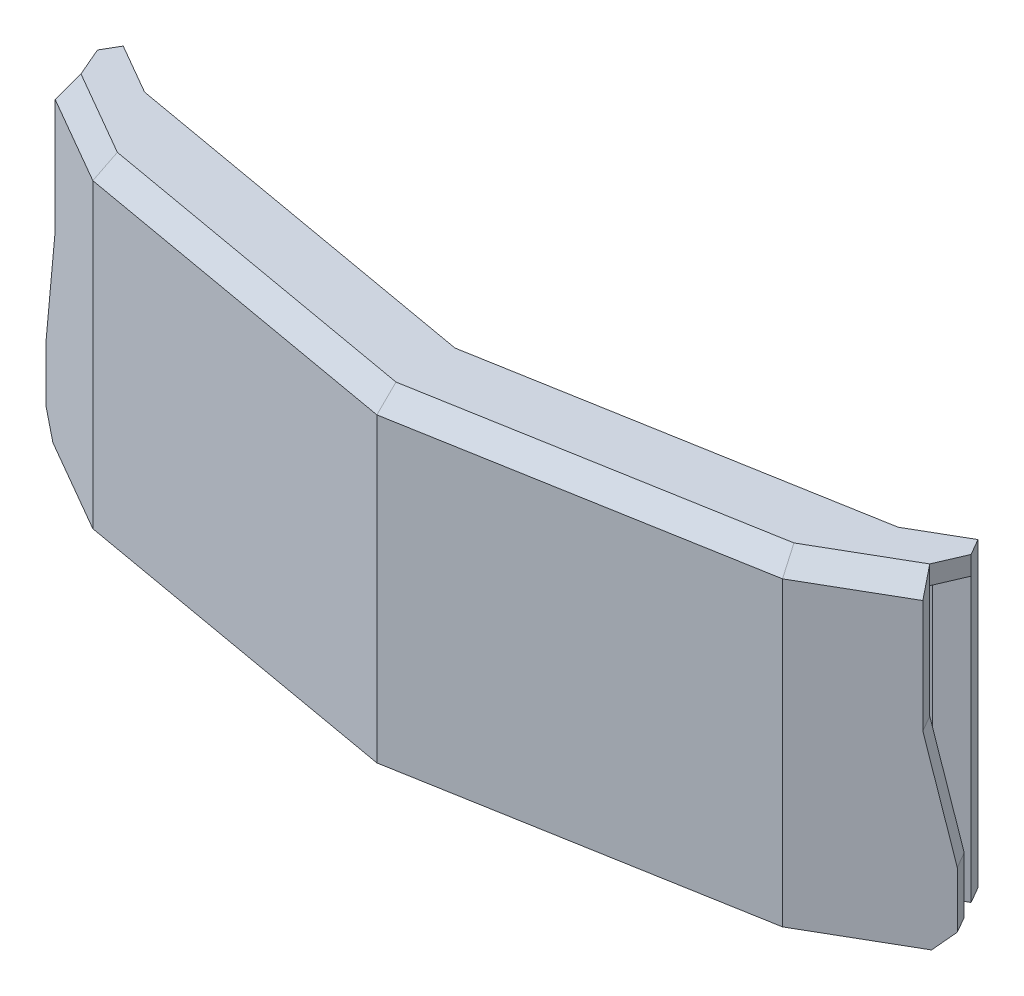
SolidWorks part; units mm, degrees
ref_plane "Front Plane" through (0, 0, 0) normal (0, 0, 1) x (1, 0, 0)
ref_plane "Top Plane" through (0, 0, 0) normal (0, 1, 0) x (1, 0, 0)
ref_plane "Right Plane" through (0, 0, 0) normal (1, 0, 0) x (0, 0, -1)
sketch "Sketch1" plane through (0, 0, 0) normal (0, 1, 0) x (1, 0, 0)
  line L0 (-46.3723, 14.6809) -> (-42.0422, 12.1809)
  line L1 (-42.0422, 12.1809) -> (-43.0422, 10.4488)
  line L2 (-43.0422, 10.4488) -> (-47.3723, 12.9488)
  line L3 (-47.3723, 12.9488) -> (-48.3723, 11.2168)
  line L4 (-48.3723, 11.2168) -> (-36.6067, 4.4239)
  line L5 (-36.6067, 4.4239) -> (0, -2.0309)
  line L6 (0, -2.0309) -> (36.6067, 4.4239)
  line L7 (46.3723, 14.6809) -> (42.0422, 12.1809)
  line L8 (42.0422, 12.1809) -> (43.0422, 10.4488)
  line L9 (43.0422, 10.4488) -> (47.3723, 12.9488)
  line L10 (47.3723, 12.9488) -> (48.3723, 11.2168)
  line L11 (48.3723, 11.2168) -> (36.6067, 4.4239)
  line L12 (-40, 8.6924) -> (-35.9121, 6.3323)
  line L13 (-35.9121, 6.3323) -> (0, 0)
  line L14 (0, 0) -> (35.9121, 6.3323)
  line L15 (35.9121, 6.3323) -> (40, 8.6924)
  line L18 (-40, 13.3112) -> (-45.3723, 16.4129)
  line L19 (-45.3723, 16.4129) -> (-46.3723, 14.6809)
  line L20 (40, 13.3112) -> (45.3723, 16.4129)
  line L21 (45.3723, 16.4129) -> (46.3723, 14.6809)
  line L22 (40, 13.3112) -> (40, 8.6924)
  line L23 (-40, 13.3112) -> (-40, 8.6924)
  dimension "D1" = 2
  dimension "D2" = 2
  dimension "D3" = 6.2034
  dimension "D4" = 2
  dimension "D5" = 80
  dimension "D6" = 2
  dimension "D7" = 6
  dimension "D8" = 6
  dimension "D9" = 13.5857
  dimension "D10" = 36.6067
  dimension "D11" = 4.4239
  dimension "D12" = 6.3323
  dimension "D13" = 13.5857
  dimension "D14" = 5
  dimension "D15" = 160
  dimension "D16" = 6.2034
  dimension "D17" = 5
  dimension "D18" = 160
  dimension "D19" = 160
extrude "Boss-Extrude2" add sketch "Sketch1" along normal blind 32
sketch "Sketch8" plane through (-6.2361, 0, 10.8012) normal (0.5, 0, -0.866) x (-0.866, 0, -0.5)
  line L25 (44.821, 32) -> (47.5, 32)
  line L26 (41.2966, 32) -> (47.5, 32) construction
  line L27 (47.5, 32) -> (47.5, 7.9443)
  line L28 (47.5, 32) -> (47.5, 0) construction
  line L29 (47.5, 7.9443) -> (44.821, 20)
  line L31 (44.821, 32) -> (44.821, 20)
  dimension "D1" = 102.529
  dimension "D2" = 12
  dimension "D3" = 2.679
sketch "Sketch9" plane through (6.2361, 0, 10.8012) normal (-0.5, 0, -0.866) x (-0.866, 0, 0.5)
  line L0 (-44.821, 20) -> (-47.5, 7.9443)
  line L2 (-47.5, 32) -> (-47.5, 0) construction
  line L3 (-47.5, 7.9443) -> (-47.5, 32)
  line L4 (-47.5, 32) -> (-44.821, 32)
  line L5 (-44.821, 32) -> (-44.821, 20)
  dimension "D1" = 102.529
  dimension "D2" = 12
  dimension "D3" = 2.679
extrude "Cut-Extrude2" cut sketch "Sketch9" against normal up to surface (2 mm away) up to face at (42.4895, 16, -7.8203)
chamfer "Chamfer3" distance 2 angle 45 2 edges at (-47.8723, 0, -12.0828) (47.8723, 0, -12.0828)
extrude "Cut-Extrude3" cut sketch "Sketch8" against normal up to surface (2 mm away) up to face at (-43.3196, 13.2, -8.2996)
sketch "Sketch11" plane through (0, 32, 0) normal (0, 1, 0) x (1, 0, 0)
  line L2 (-46.3723, 14.6809) -> (-45.3723, 16.4129)
  line L3 (-45.3723, 16.4129) -> (-40, 13.3112)
  line L6 (40, 13.3112) -> (45.3723, 16.4129)
  line L7 (45.3723, 16.4129) -> (46.3723, 14.6809)
  line L11 (36.6067, 4.4239) -> (0, -2.0309)
  line L12 (0, -2.0309) -> (-36.6067, 4.4239)
  line L14 (-40, 13.3112) -> (0, 6.2581)
  line L15 (0, 6.2581) -> (40, 13.3112)
  line L16 (36.6067, 4.4239) -> (46.0522, 9.8772)
  line L17 (46.0522, 9.8772) -> (45.0522, 11.6093)
  line L18 (45.0522, 11.6093) -> (46.3723, 14.6809)
  line L19 (-36.6067, 4.4239) -> (-46.0522, 9.8772)
  line L20 (-46.0522, 9.8772) -> (-45.0522, 11.6093)
  line L21 (-45.0522, 11.6093) -> (-46.3723, 14.6809)
extrude "Boss-Extrude4" add sketch "Sketch11" along normal blind 2
chamfer "Chamfer4" distance 2 angle 45 4 edges at (18.3034, 34, -1.1965) (-18.3034, 34, -1.1965) (41.3294, 34, -7.1506) (-41.3294, 34, -7.1506)
sketch "Sketch12" plane through (0, 0, 0) normal (0, -1, 0) x (1, 0, 0)
  line L0 (40, -8.6924) -> (43.0422, -10.4488)
  line L1 (43.0422, -10.4488) -> (47.3723, -12.9488)
  line L2 (47.3723, -12.9488) -> (45.3723, -16.4129)
  line L3 (45.3723, -16.4129) -> (40, -13.3112)
  line L4 (40, -13.3112) -> (40, -8.6924)
  line L5 (-47.3723, -12.9488) -> (-40, -8.6924)
  line L6 (-40, -8.6924) -> (-40, -13.3112)
  line L7 (-40, -13.3112) -> (-45.3723, -16.4129)
  line L8 (-45.3723, -16.4129) -> (-47.3723, -12.9488)
extrude "Cut-Extrude4" cut sketch "Sketch12" against normal blind 2
sketch "Sketch13" plane through (0, 2, 0) normal (0, -1, 0) x (1, 0, 0)
  line L0 (43.0422, -10.4488) -> (42.0422, -12.1809)
  line L1 (42.0422, -12.1809) -> (41.5422, -13.0469)
  line L2 (41.5422, -13.0469) -> (43.2742, -14.0469)
  line L3 (43.2742, -14.0469) -> (44.7742, -11.4488)
  line L4 (45.6402, -11.9488) -> (35.9121, -6.3323) construction
  line L5 (44.7742, -11.4488) -> (43.0422, -10.4488)
  line L6 (42.0422, -12.1809) -> (46.3723, -14.6809) construction
  line L7 (-43.0422, -10.4488) -> (-42.0422, -12.1809)
  line L8 (-42.0422, -12.1809) -> (-41.5422, -13.0469)
  line L9 (-41.5422, -13.0469) -> (-43.2742, -14.0469)
  line L10 (-43.2742, -14.0469) -> (-44.7742, -11.4488)
  line L11 (-43.0422, -10.4488) -> (-45.0522, -11.6093) construction
  line L12 (-44.7742, -11.4488) -> (-43.0422, -10.4488)
  line L13 (-46.3723, -14.6809) -> (-42.0422, -12.1809) construction
  dimension "D1" = 2
  dimension "D2" = 1
  dimension "D3" = 1
  dimension "D4" = 2
extrude "Cut-Extrude5" cut sketch "Sketch13" against normal up to surface (30 mm away) up to face at (0, 32, -7.8662)
